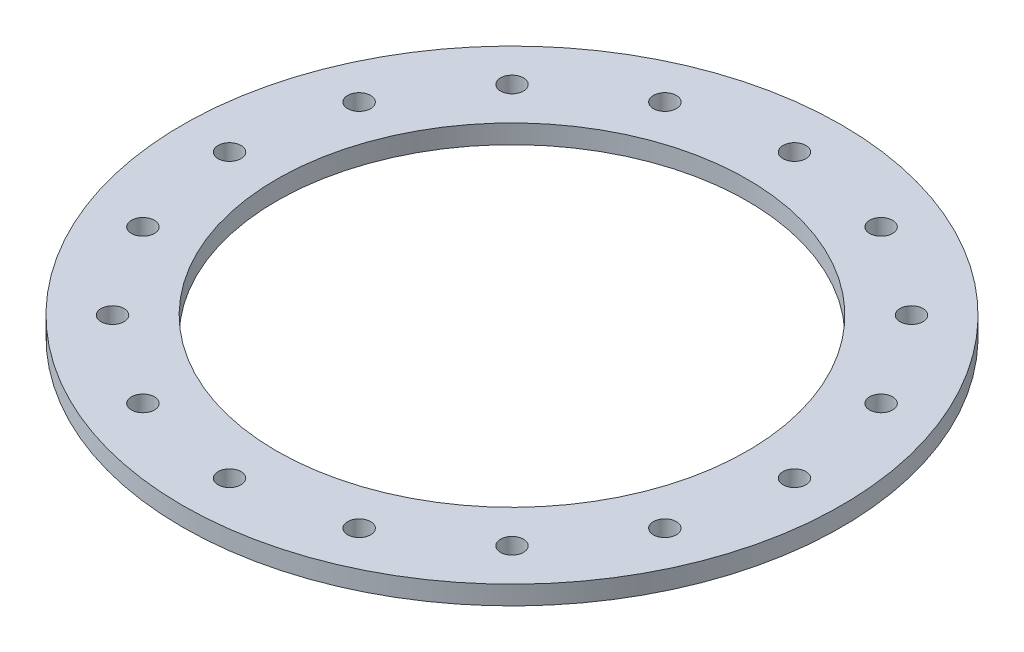
SolidWorks part; units mm, degrees
ref_plane "Front Plane" through (0, 0, 0) normal (0, 0, 1) x (1, 0, 0)
ref_plane "Top Plane" through (0, 0, 0) normal (0, 1, 0) x (1, 0, 0)
ref_plane "Right Plane" through (0, 0, 0) normal (1, 0, 0) x (0, 0, -1)
sketch "Sketch1" plane through (0, 0, 0) normal (0, 1, 0) x (1, 0, 0)
  line L0 (0, 0) -> (0, 261.7771) construction
  circle A0 centre (0, 0) radius 175
  circle A1 centre (0, 0) radius 125
  circle A2 centre (0, 150) radius 6.1
  circle A3 centre (57.4025, 138.5819) radius 6.1
  circle A4 centre (106.066, 106.066) radius 6.1
  circle A5 centre (138.5819, 57.4025) radius 6.1
  circle A6 centre (150, 0) radius 6.1
  circle A7 centre (138.5819, -57.4025) radius 6.1
  circle A8 centre (106.066, -106.066) radius 6.1
  circle A9 centre (57.4025, -138.5819) radius 6.1
  circle A10 centre (0, -150) radius 6.1
  circle A11 centre (-57.4025, -138.5819) radius 6.1
  circle A12 centre (-106.066, -106.066) radius 6.1
  circle A13 centre (-138.5819, -57.4025) radius 6.1
  circle A14 centre (-150, 0) radius 6.1
  circle A15 centre (-138.5819, 57.4025) radius 6.1
  circle A16 centre (-106.066, 106.066) radius 6.1
  circle A17 centre (-57.4025, 138.5819) radius 6.1
  point P39 (0, 0)
  dimension "D1" = 350
  dimension "D2" = 250
  dimension "D3" = 150
  dimension "D4" = 12.2
  dimension "D5" = 16
extrude "Boss-Extrude1" add sketch "Sketch1" along normal mid plane 10
